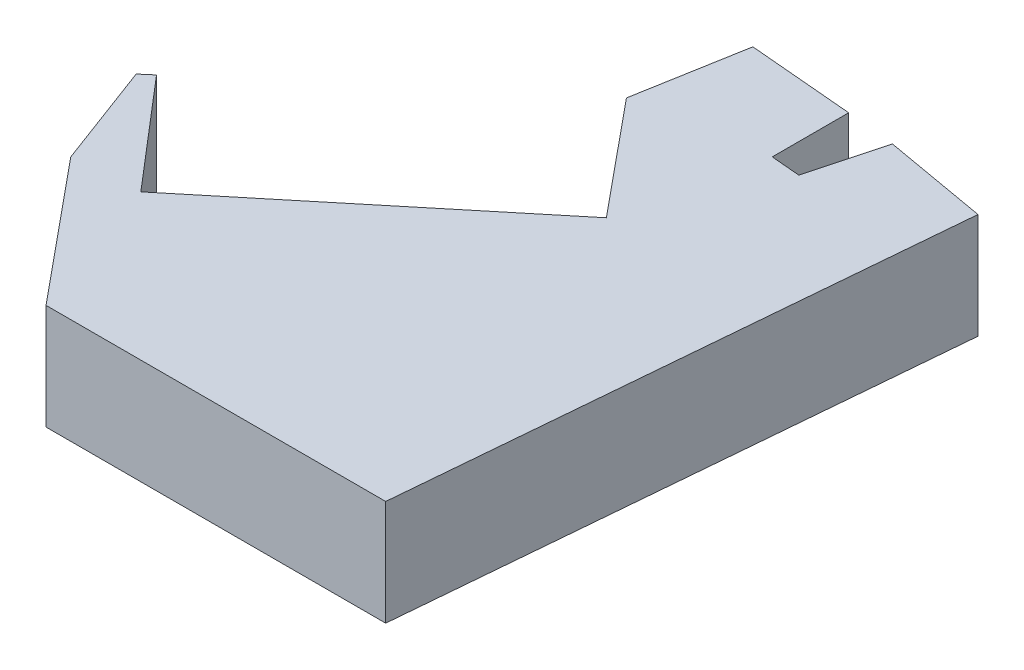
SolidWorks part; units mm, degrees
ref_plane "前视基准面" through (0, 0, 0) normal (0, 0, 1) x (1, 0, 0)
ref_plane "上视基准面" through (0, 0, 0) normal (0, 1, 0) x (1, 0, 0)
ref_plane "右视基准面" through (0, 0, 0) normal (1, 0, 0) x (0, 0, -1)
sketch "草图1" plane through (0, 0, 0) normal (0, 1, 0) x (1, 0, 0)
  line L0 (0, 0) -> (58, 0)
  line L1 (58, 0) -> (66.1364, 93)
  line L2 (66.1364, 93) -> (48.4099, 96.1257)
  line L3 (48.4099, 96.1257) -> (45.0324, 83.5207)
  line L4 (45.0324, 83.5207) -> (40.0514, 83.9564)
  line L5 (40.0514, 83.9564) -> (40.0514, 97.0061)
  line L6 (40.0514, 97.0061) -> (22.1199, 98.5749)
  line L7 (22.1199, 98.5749) -> (18.8832, 80.2186)
  line L9 (-8.6851, 24.8768) -> (34.8937, 60.7917)
  line L10 (34.8937, 60.7917) -> (18.8832, 80.2186)
  line L15 (-24.6351, 43.5036) -> (-26.5059, 41.9016)
  line L16 (-26.5059, 41.9016) -> (-19.8335, 24.0658)
  line L17 (-24.6351, 43.5036) -> (-8.6851, 24.8768)
  line L18 (0, 0) -> (-19.8335, 24.0658)
  point P11 (-17.3436, 34.9884)
  point P12 (-27.8558, 43.0418)
  point P16 (0, 0)
  point P17 (-26.5059, 41.9016)
  dimension "D1" = 18
  dimension "D2" = 18
  dimension "D4" = 95
  dimension "D5" = 95
  dimension "D7" = 93
  dimension "D3" = 5
  dimension "D8" = 58
  dimension "D9" = 95
  dimension "D10" = 95
  dimension "D11" = 95
  dimension "D12" = 95
  dimension "D6" = 13
  dimension "D13" = 13
  dimension "D14" = 100
extrude "凸台-拉伸1" add sketch "草图1" along normal blind 18
ref_point "点1"
ref_point "点2"
equation "\"sz_jd\"= 95'指根角度"
equation "\"sz_zj\"= 16'食指直径"
equation "\"zz_zj\"= 16'中指直径"
equation "\"wz_zj\"= 16'无名指直径"
equation "\"xz_zj\"= 16'小指直径"
equation "\"zg_cd\"= 13'指根长度"
equation "\"D1@草图1\"=\"zz_zj\" +2"
equation "\"D2@草图1\"=\"zz_zj\" +2"
equation "\"sz_zc\"= 93'掌长"
equation "\"D7@草图1\"= \"sz_zc\""
equation "\"sz_zdc\"= 58'掌底"
equation "\"sz_zdjd\"= 95'掌底拇指边角度"
equation "\"D8@草图1\"=\"sz_zdc\""
equation "\"D9@草图1\"=\"sz_zdjd\""
equation "\"D10@草图1\"=\"sz_jd\""
equation "\"D11@草图1\"=\"sz_jd\""
equation "\"D12@草图1\"=\"sz_jd\""
equation "\"D6@草图1\"=\"zg_cd\""
equation "\"D13@草图1\"=\"zg_cd\""
equation "\"sz_szjd\"= 100'食指中指角度"
equation "\"D14@草图1\"=\"sz_szjd\""
equation "\"D1@凸台-拉伸1\"=\"sz_zj\" +2"
